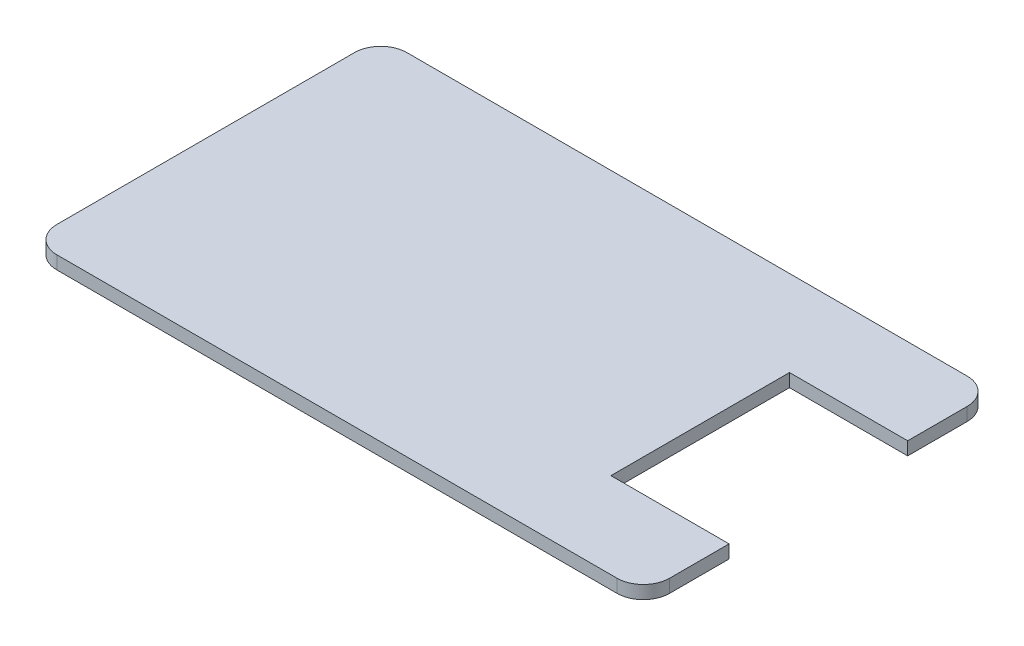
SolidWorks part; units mm, degrees
ref_plane "Спереди" through (0, 0, 0) normal (0, 0, 1) x (1, 0, 0)
ref_plane "Сверху" through (0, 0, 0) normal (0, 1, 0) x (1, 0, 0)
ref_plane "Справа" through (0, 0, 0) normal (1, 0, 0) x (0, 0, -1)
sketch "Эскиз1" plane through (0, 0, 0) normal (0, 1, 0) x (1, 0, 0)
  line L1 (35, -20) -> (-35, -20)
  line L2 (35, -20) -> (35, 20)
  line L3 (35, 20) -> (-35, 20)
  line L4 (-35, -20) -> (-35, 20)
  line L5 (35, -20) -> (-35, 20) construction
  line L6 (35, 20) -> (-35, -20) construction
  point P0 (0, 0)
  dimension "D1" = 70
  dimension "D2" = 40
extrude "Бобышка-Вытянуть1" add sketch "Эскиз1" along normal blind 1.5
fillet "Скругление1" radius 3 4 edges at (-35, 0.75, -20) (35, 0.75, -20) (35, 0.75, 20) (-35, 0.75, 20)
sketch "Эскиз2" plane through (0, 1.5, 0) normal (0, 1, 0) x (1, 0, 0)
  line L0 (35, -17) -> (35, 17) construction
  line L1 (35, 10.2) -> (21.5, 10.2)
  line L2 (35, 10.2) -> (35, -10.2)
  line L3 (35, -10.2) -> (21.5, -10.2)
  line L4 (21.5, 10.2) -> (21.5, -10.2)
  line L5 (32, 20) -> (-32, 20) construction
  line L6 (-32, -20) -> (32, -20) construction
  dimension "D1" = 13.5
  dimension "D2" = 9.8
  dimension "D3" = 9.8
extrude "Вырез-Вытянуть1" cut sketch "Эскиз2" against normal through all
